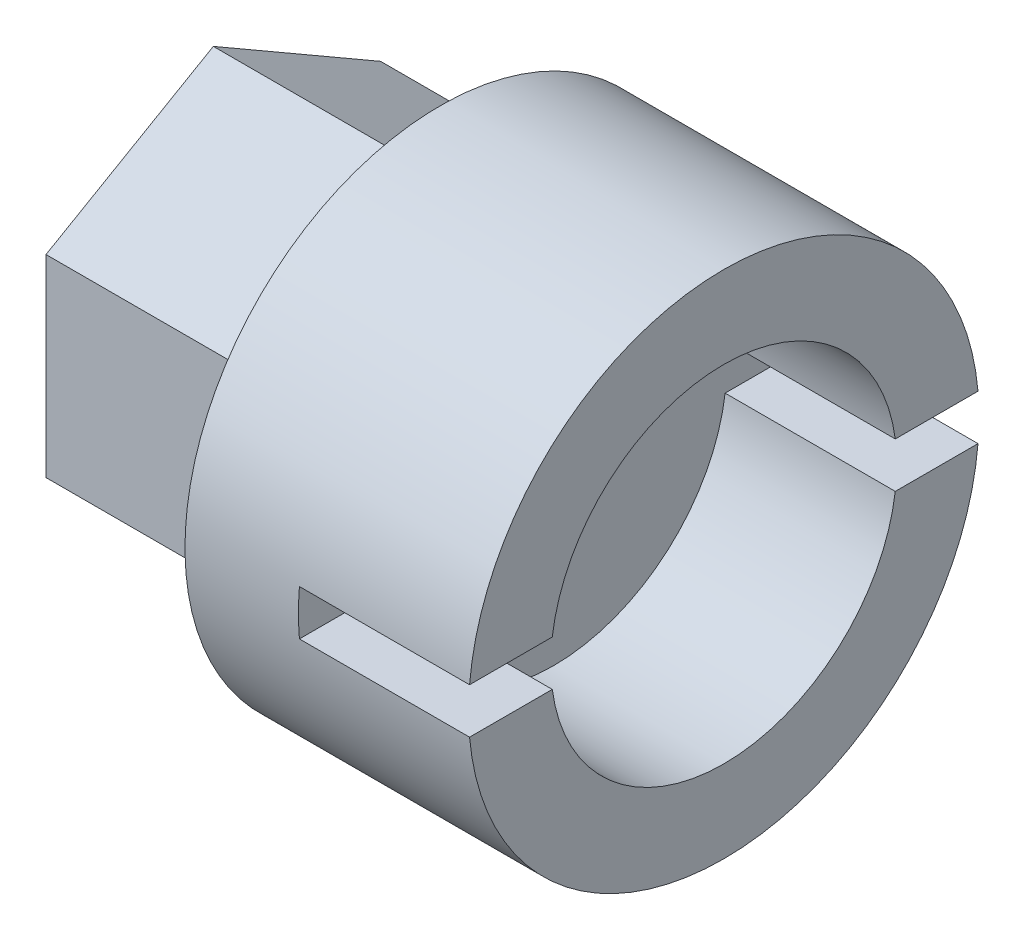
SolidWorks part; units mm, degrees
ref_plane "Front Plane" through (0, 0, 0) normal (1, 0, 0) x (0, 1, 0)
ref_plane "Top Plane" through (0, 0, 0) normal (0, 0, 1) x (0, 1, 0)
ref_plane "Right Plane" through (0, 0, 0) normal (0, 1, 0) x (-1, 0, 0)
sketch "Sketch1" plane through (0, 0, 0) normal (1, 0, 0) x (0, 1, 0)
  line L1 (1.7032, -2.95) -> (3.4064, 0)
  line L2 (3.4064, 0) -> (1.7032, 2.95)
  line L3 (1.7032, 2.95) -> (-1.7032, 2.95)
  line L4 (-1.7032, 2.95) -> (-3.4064, 0)
  line L5 (-3.4064, 0) -> (-1.7032, -2.95)
  line L6 (-1.7032, -2.95) -> (1.7032, -2.95)
  circle A0 centre (0, 0) radius 2.95 construction
  point P1 (1.5025, 2.5303)
  dimension "D1" = 5.9
extrude "Boss-Extrude1" add sketch "Sketch1" along normal blind 4
sketch "Sketch2" plane through (4, 0, 0) normal (1, 0, 0) x (0, 1, 0)
  circle A0 centre (0, 0) radius 4.5
  point P3 (0, 0)
  dimension "D1" = 9
extrude "Boss-Extrude2" add sketch "Sketch2" along normal blind 2
sketch "Sketch3" plane through (6, 0, 0) normal (1, 0, 0) x (0, 1, 0)
  circle A0 centre (0, 0) radius 4.5
  circle A1 centre (0, 0) radius 3.05
  circle A3 centre (0, 0) radius 4.5 construction
  dimension "D1" = 6.1
extrude "Boss-Extrude3" add sketch "Sketch3" along normal blind 3
sketch "Sketch4" plane through (0, 0, 0) normal (0, 0, 1) x (0, 1, 0)
  line L0 (-4.5, -9) -> (4.5, -9) construction
  line L1 (-0.4, -6) -> (0.4, -6)
  line L2 (-0.4, -6) -> (-0.4, -9)
  line L3 (-0.4, -9) -> (0.4, -9)
  line L4 (0.4, -6) -> (0.4, -9)
  line L5 (-0.4, -6) -> (0.4, -9) construction
  line L6 (-0.4, -9) -> (0.4, -6) construction
  point P0 (0, -7.5)
  dimension "D1" = 3
  dimension "D2" = 0.8
extrude "Cut-Extrude1" cut sketch "Sketch4" against normal mid plane 10
